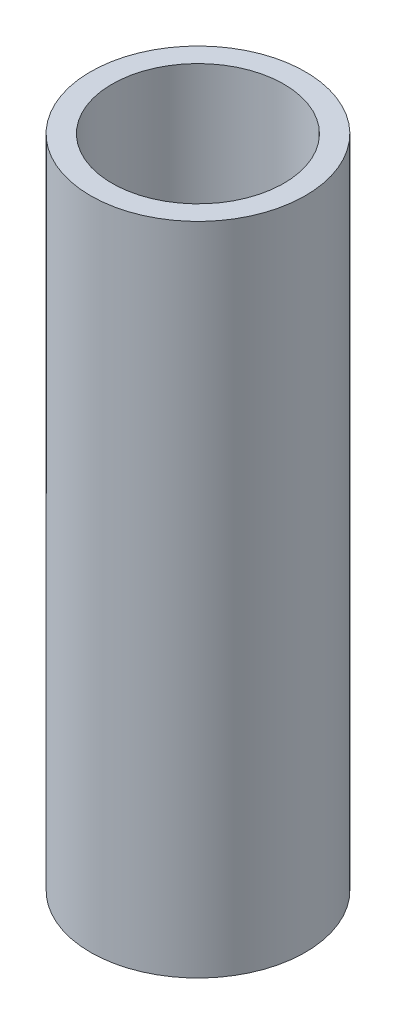
SolidWorks part; units mm, degrees
ref_plane "Front Plane" through (0, 0, 0) normal (0, 0, 1) x (1, 0, 0)
ref_plane "Top Plane" through (0, 0, 0) normal (0, 1, 0) x (1, 0, 0)
ref_plane "Right Plane" through (0, 0, 0) normal (1, 0, 0) x (0, 0, -1)
sketch "Sketch1" plane through (0, 0, 0) normal (0, 1, 0) x (1, 0, 0)
  circle A0 centre (0, 0) radius 10
  circle A1 centre (0, 0) radius 2.65
  dimension "D1" = 20
  dimension "D2" = 5.3
extrude "Boss-Extrude1" add sketch "Sketch1" along normal blind 3
sketch "Sketch2" plane through (0, 3, 0) normal (0, 1, 0) x (1, 0, 0)
  circle A0 centre (0, 0) radius 10 construction
  circle A1 centre (0, 0) radius 10
  circle A3 centre (0, 0) radius 8
  dimension "D1" = 2
extrude "Boss-Extrude2" add sketch "Sketch2" along normal blind 58
